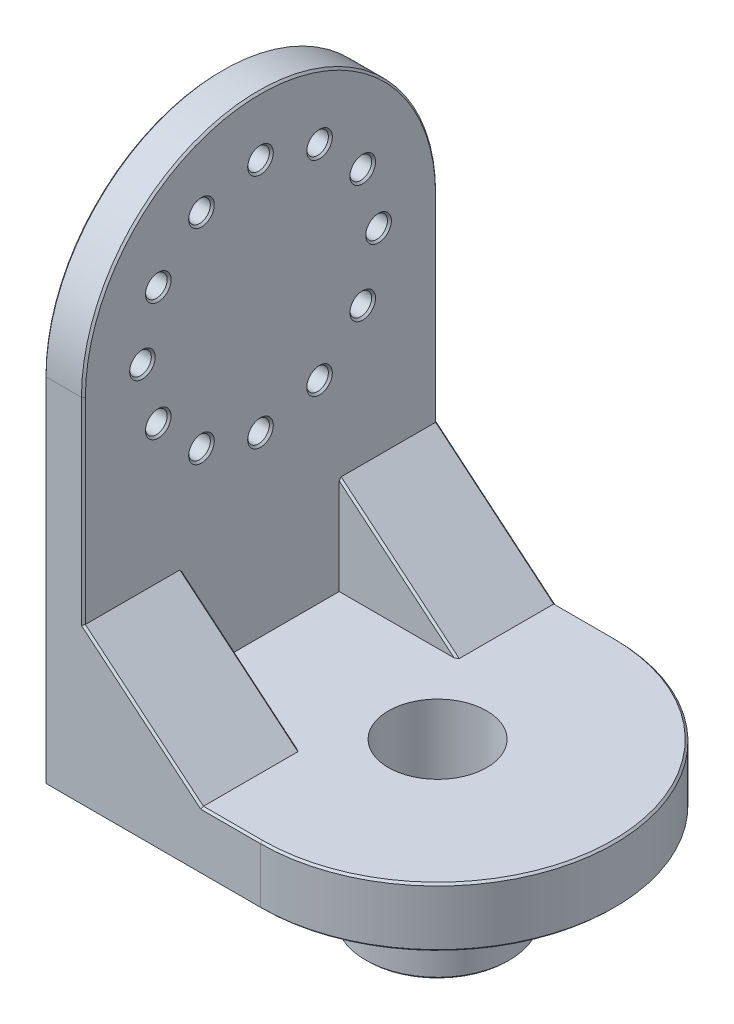
SolidWorks part; units mm, degrees
ref_plane "前视基准面" through (0, 0, 0) normal (0, 0, 1) x (1, 0, 0)
ref_plane "上视基准面" through (0, 0, 0) normal (0, 1, 0) x (1, 0, 0)
ref_plane "右视基准面" through (0, 0, 0) normal (1, 0, 0) x (0, 0, -1)
other "Configuration Table"
sketch "草图1" plane through (0, 0, 0) normal (1, 0, 0) x (0, 0, -1)
  circle A0 centre (0, 0) radius 45
  dimension "D1" = 90
extrude "凸台-拉伸1" add sketch "草图1" along normal blind 10
sketch "草图2" plane through (10, 0, 0) normal (1, 0, 0) x (0, 0, -1)
  line L0 (0, 0) -> (50000, 0) construction
  line L1 (0, 0) -> (25000, 43301.2702) construction
  line L2 (0, 0) -> (43301.2702, 25000) construction
  line L3 (0, 0) -> (0, -50000) construction
  circle A0 centre (0, 0) radius 30 construction
  circle A1 centre (0, 30) radius 2.75
  circle A2 centre (30, 0) radius 2.75
  circle A3 centre (0, -30) radius 2.75
  circle A4 centre (-30, 0) radius 2.75
  circle A5 centre (25.9808, 15) radius 2.75
  circle A6 centre (15, 25.9808) radius 2.75
  circle A7 centre (-15, 25.9808) radius 2.75
  circle A8 centre (-25.9808, 15) radius 2.75
  circle A9 centre (-25.9808, -15) radius 2.75
  circle A10 centre (-15, -25.9808) radius 2.75
  circle A11 centre (15, -25.9808) radius 2.75
  circle A12 centre (25.9808, -15) radius 2.75
  point P14 (0, 0)
  point P22 (25.9808, 15)
  dimension "D1" = 60
  dimension "D2" = 5.5
  dimension "D4" = 30
  dimension "D5" = 30
  dimension "D3" = 4
extrude "切除-拉伸1" cut sketch "草图2" against normal through all
sketch "草图3" plane through (10, 0, 0) normal (1, 0, 0) x (0, 0, -1)
  line L0 (-45, 0) -> (-45, -80)
  line L1 (-45, -80) -> (45, -80)
  line L2 (45, -80) -> (45, 0)
  circle A1 centre (0, 0) radius 45
  circle A2 centre (0, 0) radius 45
  circle M7 centre (0, 0) radius 45
  dimension "D2" = 80
  dimension "D1" = 0
extrude "凸台-拉伸2" add sketch "草图3" against normal blind 5 contours L1 L2 L0 M7
sketch "草图4" plane through (0, -80, 0) normal (0, -1, 0) x (1, 0, 0)
  line L0 (10, 45) -> (55, 45)
  line L1 (10, -45) -> (55, -45)
  line L2 (10, 45) -> (10, -45)
  arc A0 (55, -45) -> (55, 45) centre (55, 0) ccw
  dimension "D1" = 90
  dimension "D2" = 55
extrude "凸台-拉伸3" add sketch "草图4" against normal blind 5
sketch "草图5" plane through (0, -80, 0) normal (0, -1, 0) x (1, 0, 0)
  line L3 (5, -45) -> (55, -45)
  line L4 (55, 45) -> (5, 45)
  line L5 (5, 45) -> (5, -45)
  line L6 (5, -45) -> (55, -45)
  line L7 (55, 45) -> (5, 45)
  line L8 (5, 45) -> (5, -45)
  arc A1 (55, -45) -> (55, 45) centre (55, 0) ccw
  arc A2 (55, -45) -> (55, 45) centre (55, 0) ccw
  dimension "D1" = 0
extrude "凸台-拉伸4" add sketch "草图5" along normal blind 10
sketch "草图6" plane through (0, -90, 0) normal (0, -1, 0) x (1, 0, 0)
  circle A0 centre (55, 0) radius 18.25
  dimension "D1" = 36.5
extrude "凸台-拉伸5" add sketch "草图6" along normal blind 25
sketch "草图7" plane through (0, 0, -45) normal (0, 0, -1) x (-1, 0, 0)
  line L0 (-40, -75) -> (-10, -50)
  line L1 (-10, -75) -> (-55, -75) construction
  line L2 (-10, -75) -> (-10, 0) construction
  line L3 (-10, -50) -> (-10, -75)
  line L4 (-10, -75) -> (-40, -75)
  dimension "D1" = 25
  dimension "D2" = 30
extrude "凸台-拉伸6" add sketch "草图7" against normal blind 25
sketch "草图8" plane through (0, 0, 45) normal (0, 0, 1) x (1, 0, 0)
  line L3 (10, -75) -> (40, -75)
  line L4 (40, -75) -> (10, -50)
  line L5 (10, -50) -> (10, -75)
  line L6 (10, -75) -> (40, -75)
  line L7 (40, -75) -> (10, -50)
  line L8 (10, -50) -> (10, -75)
  dimension "D1" = 0
extrude "凸台-拉伸7" add sketch "草图8" against normal blind 25
sketch "草图9" plane through (5, 0, 0) normal (-1, 0, 0) x (0, 0, 1)
  line L3 (-45, 0) -> (-45, -90)
  line L4 (-45, -90) -> (45, -90)
  line L5 (45, -90) -> (45, 0)
  line L6 (-45, 0) -> (-45, -90)
  line L7 (-45, -90) -> (45, -90)
  line L8 (45, -90) -> (45, 0)
  arc A1 (-45, 0) -> (45, 0) centre (0, 0) ccw
  arc A2 (-45, 0) -> (45, 0) centre (0, 0) ccw
  dimension "D1" = 0
extrude "凸台-拉伸8" add sketch "草图9" along normal blind 5
chamfer "倒角1" distance 0.5 angle 45 1 edges at (55, -115, -18.25)
chamfer "倒角2" distance 0.5 angle 45 12 edges at (10, -15, 23.2308) (10, -25.9808, 12.25) (10, -30, -2.75) (10, -25.9808, -12.25) (10, -15, -23.2308) (10, 0, -32.75) (10, 15, -28.7308) (10, 25.9808, -17.75) (10, 30, -2.75) (10, 25.9808, 17.75) (10, 15, 28.7308) (10, 0, 27.25)
chamfer "倒角3" distance 0.5 angle 45 16 edges at (0, -45, 45) (0, -90, 0) (0, -45, -45) (0, 45, 0) (0, 30, -2.75) (0, -15, -23.2308) (0, -25.9808, -12.25) (0, -25.9808, 12.25) (0, 15, -28.7308) (0, 0, 27.25) (0, -30, -2.75) (0, 0, -32.75) (0, 25.9808, -17.75) (0, 25.9808, 17.75) (0, 15, 28.7308) (0, -15, 23.2308)
chamfer "倒角4" distance 0.5 angle 45 3 edges at (10, -25, -45) (10, -25, 45) (10, 45, 0)
chamfer "倒角5" distance 0.5 angle 45 10 edges at (25, -62.5, 20) (25, -62.5, -20) (24.75, -62.2917, -45) (27.75, -90, -45) (27.75, -90, 45) (100, -90, 0) (100, -75, 0) (47.5, -75, -45) (47.5, -75, 45) (24.75, -62.2917, 45)
sketch "草图10" plane through (0, -115, 0) normal (0, -1, 0) x (1, 0, 0)
  circle A0 centre (55, 0) radius 12.5
  dimension "D1" = 25
extrude "切除-拉伸2" cut sketch "草图10" against normal through all
